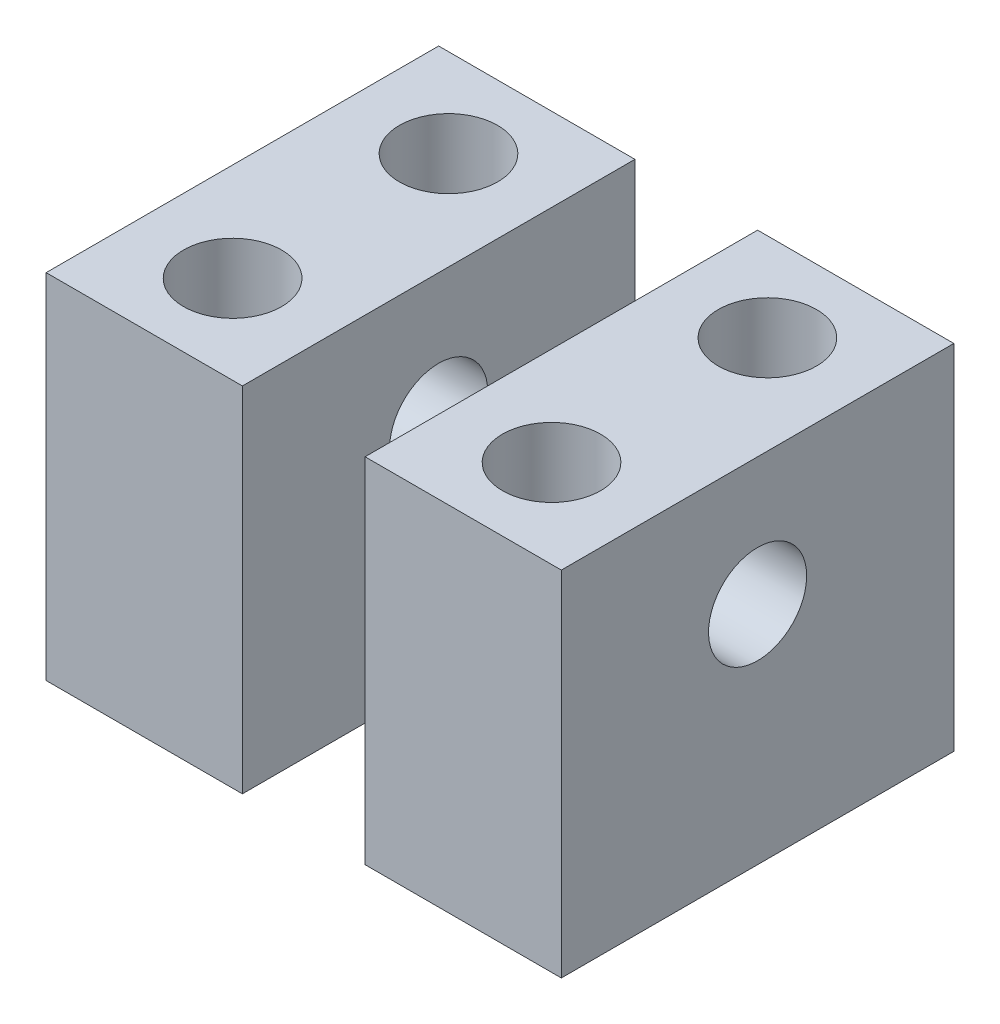
SolidWorks part; units mm, degrees
ref_plane "Front Plane" through (0, 0, 0) normal (0, 0, 1) x (1, 0, 0)
ref_plane "Top Plane" through (0, 0, 0) normal (0, 1, 0) x (1, 0, 0)
ref_plane "Right Plane" through (0, 0, 0) normal (1, 0, 0) x (0, 0, -1)
sketch "Sketch2" plane through (0, 0, 0) normal (0, 0, 1) x (1, 0, 0)
  line L0 (0, 0) -> (0, 18)
  line L1 (0, 18) -> (10, 18)
  line L2 (10, 18) -> (10, 3)
  line L3 (10, 3) -> (16.25, 3)
  line L4 (16.25, 3) -> (16.25, 18)
  line L5 (16.25, 18) -> (26.25, 18)
  line L6 (26.25, 18) -> (26.25, 0)
  line L7 (26.25, 0) -> (0, 0)
  point P4 (16.25, 2.0955)
  point P10 (0, 0)
  dimension "D1" = 6.25
  dimension "D2" = 10
  dimension "D3" = 15
  dimension "D4" = 3
extrude "Boss-Extrude1" add sketch "Sketch2" along normal blind 20
sketch "Sketch3" plane through (0, 18, 0) normal (0, 1, 0) x (1, 0, 0)
  line L0 (13.125, 0) -> (13.125, -20) construction
  line L1 (16.25, 0) -> (10, 0) construction
  line L2 (16.25, -20) -> (10, -20) construction
  line L3 (21.25, 0) -> (21.25, -20) construction
  line L4 (26.25, 0) -> (16.25, 0) construction
  line L5 (26.25, -20) -> (16.25, -20) construction
  line L6 (26.25, -15.5) -> (21.25, -15.5) construction
  line L7 (26.25, -20) -> (26.25, 0) construction
  line L8 (26.25, -15.5) -> (26.25, -20) construction
  line L9 (21.25, -10) -> (26.25, -10) construction
  circle A0 centre (21.25, -15.5) radius 2.5
  circle A1 centre (21.25, -4.5) radius 2.5
  circle A2 centre (5, -15.5) radius 2.5
  circle A3 centre (5, -4.5) radius 2.5
  dimension "D1" = 5
  dimension "D2" = 4.5
extrude "Cut-Extrude1" cut sketch "Sketch3" against normal through all
sketch "Sketch4" plane through (26.25, 0, 0) normal (1, 0, 0) x (0, 0, -1)
  line L1 (-20, 3) -> (0, 3) construction
  line L2 (-20, 3) -> (0, 3) construction
  circle A0 centre (-10, 11.5) radius 2.5
  point P0 (-10, 3)
  dimension "D1" = 5
  dimension "D2" = 8.5
extrude "Cut-Extrude4" cut sketch "Sketch4" against normal through all
sketch "Sketch5" plane through (0, 3, 0) normal (0, 1, 0) x (1, 0, 0)
  line L4 (16.25, 0) -> (10, 0)
  line L5 (10, 0) -> (10, -20)
  line L6 (10, -20) -> (16.25, -20)
  line L7 (16.25, -20) -> (16.25, 0)
  line L8 (16.25, 0) -> (10, 0)
  line L9 (10, 0) -> (10, -20)
  line L10 (10, -20) -> (16.25, -20)
  line L11 (16.25, -20) -> (16.25, 0)
  dimension "D1" = 0
extrude "Cut-Extrude5" cut sketch "Sketch5" against normal through all
